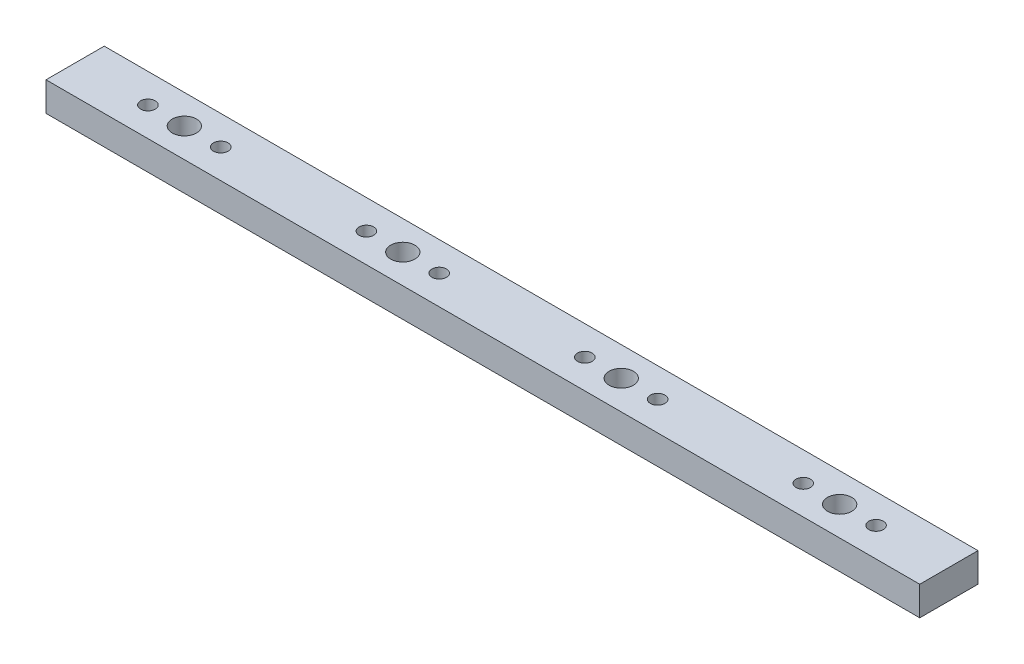
SolidWorks part; units mm, degrees
material "HDPE-green"
ref_plane "Front Plane" through (0, 0, 0) normal (0, 0, 1) x (1, 0, 0)
ref_plane "Top Plane" through (0, 0, 0) normal (0, 1, 0) x (1, 0, 0)
ref_plane "Right Plane" through (0, 0, 0) normal (1, 0, 0) x (0, 0, -1)
sketch "Sketch1" plane through (0, 0, 0) normal (0, 1, 0) x (1, 0, 0)
  line L1 (-180, -12) -> (180, -12)
  line L2 (-180, -12) -> (-180, 12)
  line L3 (-180, 12) -> (180, 12)
  line L4 (180, -12) -> (180, 12)
  line L5 (-180, -12) -> (180, 12) construction
  line L6 (-180, 12) -> (180, -12) construction
  point P0 (0, 0)
  dimension "D1" = 24
  dimension "D2" = 360
extrude "Boss-Extrude1" add sketch "Sketch1" along normal blind 12
sketch "Sketch2" plane through (0, 12, 0) normal (0, 1, 0) x (1, 0, 0)
  line L0 (-180, 12) -> (-180, -12) construction
  circle A0 centre (-150, 0) radius 3
  circle A1 centre (-120, 0) radius 3
  circle A2 centre (-135, 0) radius 5
  dimension "D1" = 6
  dimension "D3" = 6
  dimension "D5" = 10
  dimension "D2" = 30
  dimension "D4" = 60
  dimension "D6" = 15
extrude "Cut-Extrude1" cut sketch "Sketch2" against normal up to next
pattern_linear "LPattern1" count 4 spacing 90 along (1, 0, 0) of "Cut-Extrude1"
